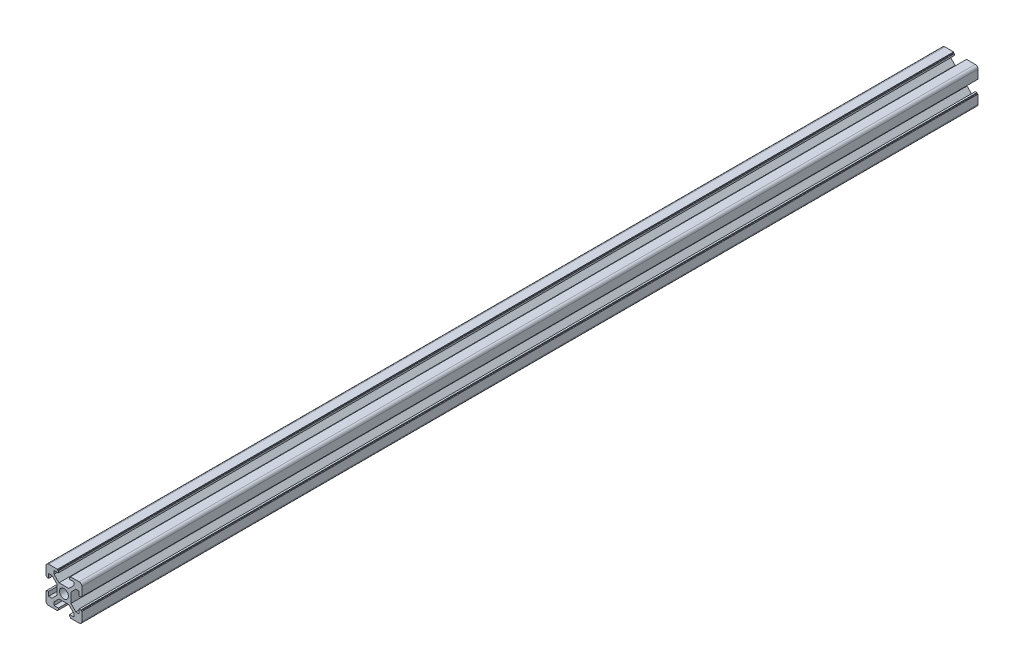
SolidWorks part; units mm, degrees
material "6061 合金"
ref_plane "前视基准面" through (0, 0, 0) normal (0, 0, 1) x (1, 0, 0)
ref_plane "上视基准面" through (0, 0, 0) normal (0, 1, 0) x (1, 0, 0)
ref_plane "右视基准面" through (0, 0, 0) normal (1, 0, 0) x (0, 0, -1)
sketch "草图1" plane through (0, 0, 0) normal (0, 0, 1) x (1, 0, 0)
  line B0 (8.5, 10) -> (3.6, 10)
  line B1 (10, 3.6) -> (10, 8.5)
  line B2 (9.5, 3.6) -> (10, 3.6)
  line B3 (9.5, 3.1) -> (9.5, 3.6)
  line B4 (8.5, 3.1) -> (9.5, 3.1)
  line B5 (8.5, 5.5) -> (8.5, 3.1)
  line B6 (6.65, 5.5) -> (8.5, 5.5)
  line B7 (3.9, 2.75) -> (6.65, 5.5)
  line B8 (3.9, -2.75) -> (3.9, 2.75)
  line B9 (6.65, -5.5) -> (3.9, -2.75)
  line B10 (8.5, -5.5) -> (6.65, -5.5)
  line B11 (8.5, -3.1) -> (8.5, -5.5)
  line B12 (9.5, -3.1) -> (8.5, -3.1)
  line B13 (9.5, -3.6) -> (9.5, -3.1)
  line B14 (10, -3.6) -> (9.5, -3.6)
  line B15 (10, -8.5) -> (10, -3.6)
  line B16 (3.6, -10) -> (8.5, -10)
  line B17 (3.6, -9.5) -> (3.6, -10)
  line B18 (3.1, -9.5) -> (3.6, -9.5)
  line B19 (3.1, -8.5) -> (3.1, -9.5)
  line B20 (5.5, -8.5) -> (3.1, -8.5)
  line B21 (5.5, -6.65) -> (5.5, -8.5)
  line B22 (2.75, -3.9) -> (5.5, -6.65)
  line B23 (-2.75, -3.9) -> (2.75, -3.9)
  line B24 (-5.5, -6.65) -> (-2.75, -3.9)
  line B25 (-5.5, -8.5) -> (-5.5, -6.65)
  line B26 (-3.1, -8.5) -> (-5.5, -8.5)
  line B27 (-3.1, -9.5) -> (-3.1, -8.5)
  line B28 (-3.6, -9.5) -> (-3.1, -9.5)
  line B29 (-3.6, -10) -> (-3.6, -9.5)
  line B30 (-8.5, -10) -> (-3.6, -10)
  line B31 (-10, -3.6) -> (-10, -8.5)
  line B32 (-9.5, -3.6) -> (-10, -3.6)
  line B33 (-9.5, -3.1) -> (-9.5, -3.6)
  line B34 (-8.5, -3.1) -> (-9.5, -3.1)
  line B35 (-8.5, -5.5) -> (-8.5, -3.1)
  line B36 (-6.65, -5.5) -> (-8.5, -5.5)
  line B37 (-3.9, -2.75) -> (-6.65, -5.5)
  line B38 (-3.9, 2.75) -> (-3.9, -2.75)
  line B39 (-6.65, 5.5) -> (-3.9, 2.75)
  line B40 (-8.5, 5.5) -> (-6.65, 5.5)
  line B41 (-8.5, 3.1) -> (-8.5, 5.5)
  line B42 (-9.5, 3.1) -> (-8.5, 3.1)
  line B43 (-9.5, 3.6) -> (-9.5, 3.1)
  line B44 (-10, 3.6) -> (-9.5, 3.6)
  line B45 (-10, 8.5) -> (-10, 3.6)
  line B46 (-3.6, 10) -> (-8.5, 10)
  line B47 (-3.6, 9.5) -> (-3.6, 10)
  line B48 (-3.1, 9.5) -> (-3.6, 9.5)
  line B49 (-3.1, 8.5) -> (-3.1, 9.5)
  line B50 (-5.5, 8.5) -> (-3.1, 8.5)
  line B51 (-5.5, 6.65) -> (-5.5, 8.5)
  line B52 (-2.75, 3.9) -> (-5.5, 6.65)
  line B53 (2.75, 3.9) -> (-2.75, 3.9)
  line B54 (5.5, 6.65) -> (2.75, 3.9)
  line B55 (5.5, 8.5) -> (5.5, 6.65)
  line B56 (3.1, 8.5) -> (5.5, 8.5)
  line B57 (3.1, 9.5) -> (3.1, 8.5)
  line B58 (3.6, 9.5) -> (3.1, 9.5)
  line B59 (3.6, 10) -> (3.6, 9.5)
  arc B60 (-2.5, 0) -> (2.5, 0) centre (0, 0) ccw
  arc B61 (2.5, 0) -> (-2.5, 0) centre (0, 0) ccw
  arc B62 (10, 8.5) -> (8.5, 10) centre (8.5, 8.5) ccw
  arc B63 (8.5, -10) -> (10, -8.5) centre (8.5, -8.5) ccw
  arc B64 (-10, -8.5) -> (-8.5, -10) centre (-8.5, -8.5) ccw
  arc B65 (-8.5, 10) -> (-10, 8.5) centre (-8.5, 8.5) ccw
sketch_block_instance "2020铝型材-1"
sketch_block "2020铝型材"
extrude "凸台-拉伸1" add sketch "草图1" along normal blind 500
